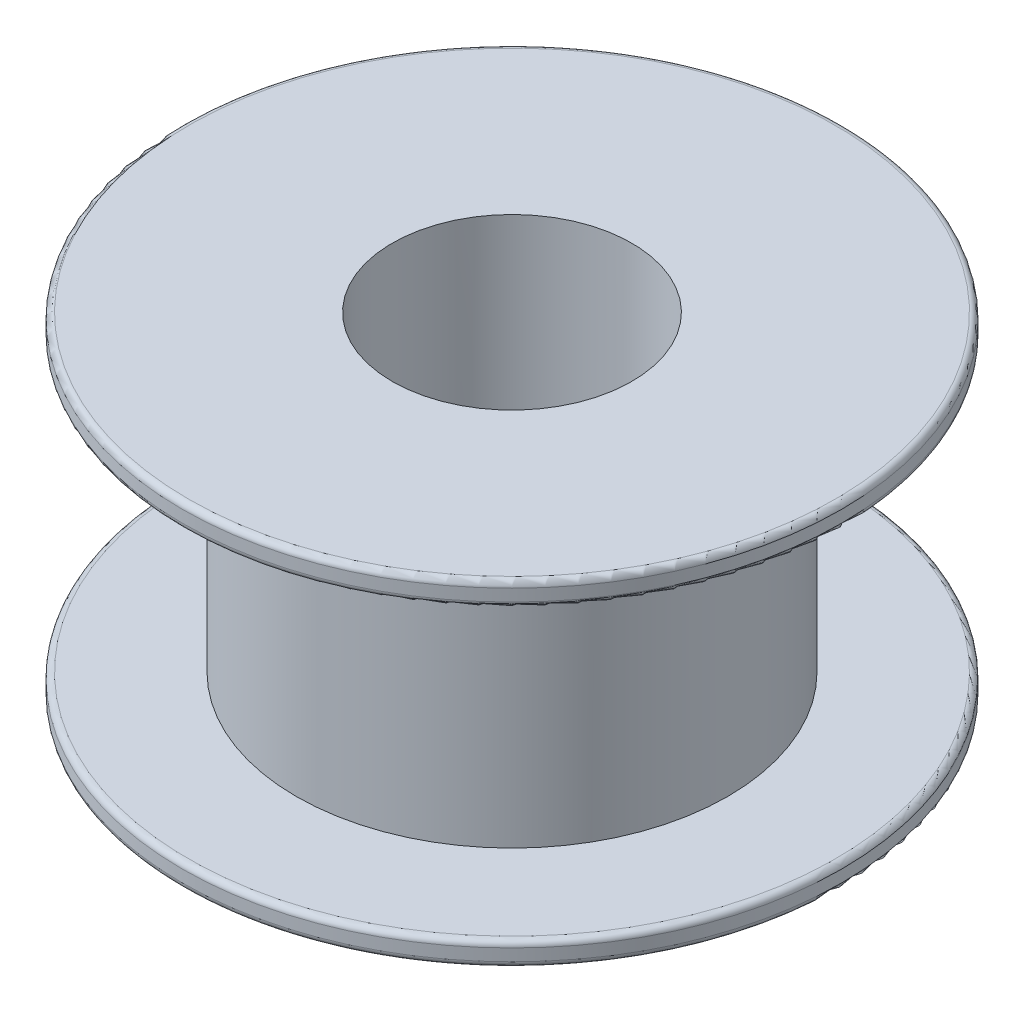
SolidWorks part; units mm, degrees
material "ABS"
ref_plane "前视基准面" through (0, 0, 0) normal (0, 0, 1) x (1, 0, 0)
ref_plane "上视基准面" through (0, 0, 0) normal (0, 1, 0) x (1, 0, 0)
ref_plane "右视基准面" through (0, 0, 0) normal (1, 0, 0) x (0, 0, -1)
other "Configuration Table"
sketch "草图1" plane through (0, 0, 0) normal (0, 1, 0) x (1, 0, 0)
  circle A0 centre (0, 0) radius 27.5
  circle A1 centre (0, 0) radius 10
  dimension "D1" = 55
  dimension "D2" = 20
extrude "凸台-拉伸1" add sketch "草图1" against normal blind 2
sketch "草图2" plane through (0, -2, 0) normal (0, -1, 0) x (1, 0, 0)
  circle A0 centre (0, 0) radius 18
  circle A1 centre (0, 0) radius 10 construction
  circle A2 centre (0, 0) radius 10
  dimension "D1" = 36
extrude "凸台-拉伸2" add sketch "草图2" along normal blind 24
sketch "草图3" plane through (0, -26, 0) normal (0, -1, 0) x (1, 0, 0)
  circle A0 centre (0, 0) radius 27.5 construction
  circle A1 centre (0, 0) radius 27.5
  circle A2 centre (0, 0) radius 10 construction
  circle A3 centre (0, 0) radius 10
extrude "凸台-拉伸3" add sketch "草图3" along normal blind 2
fillet "圆角1" radius 0.5 4 edges at (0, -2, 27.5) (0, 0, 27.5) (0, -26, -27.5) (0, -28, -27.5)
